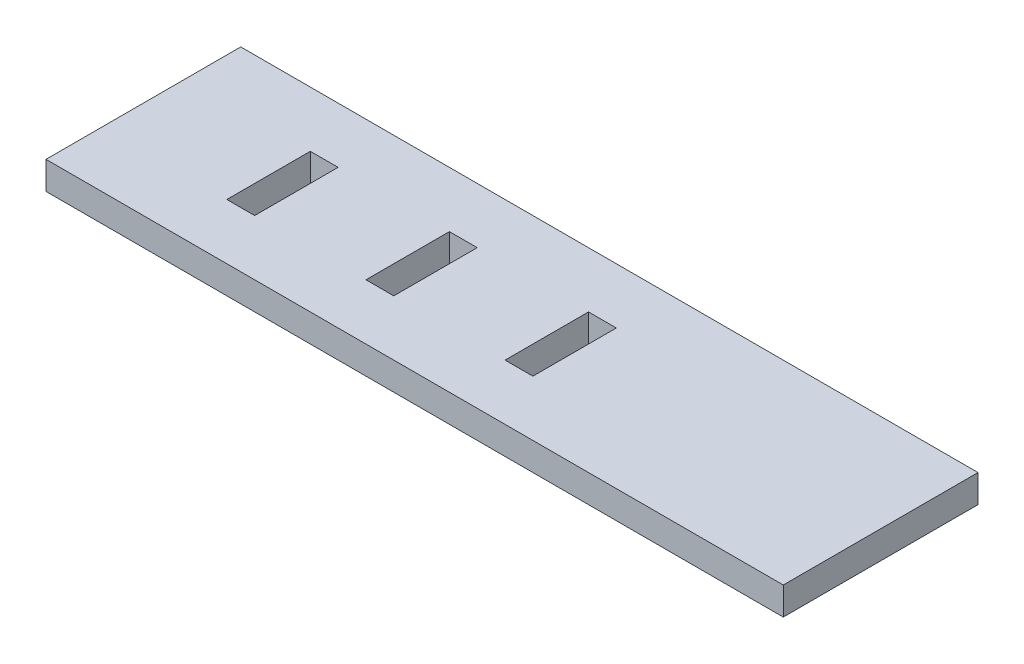
SolidWorks part; units mm, degrees
ref_plane "Front Plane" through (0, 0, 0) normal (0, 0, 1) x (1, 0, 0)
ref_plane "Top Plane" through (0, 0, 0) normal (0, 1, 0) x (1, 0, 0)
ref_plane "Right Plane" through (0, 0, 0) normal (1, 0, 0) x (0, 0, -1)
sketch "Sketch1" plane through (0, 0, 0) normal (0, 1, 0) x (1, 0, 0)
  line L1 (-98.4247, 43.4932) -> (166.5753, 43.4932)
  line L2 (-98.4247, 43.4932) -> (-98.4247, -26.5068)
  line L3 (-98.4247, -26.5068) -> (166.5753, -26.5068)
  line L4 (166.5753, 43.4932) -> (166.5753, -26.5068)
  line L6 (-53.4247, 23.4932) -> (-43.4247, 23.4932)
  line L7 (-53.4247, 23.4932) -> (-53.4247, -6.5068)
  line L8 (-53.4247, -6.5068) -> (-43.4247, -6.5068)
  line L9 (-43.4247, 23.4932) -> (-43.4247, -6.5068)
  line L13 (6.5753, 23.4932) -> (-3.4247, 23.4932)
  line L14 (6.5753, 23.4932) -> (6.5753, -6.5068)
  line L15 (6.5753, -6.5068) -> (-3.4247, -6.5068)
  line L16 (-3.4247, 23.4932) -> (-3.4247, -6.5068)
  line L21 (46.5753, 23.4932) -> (56.5753, 23.4932)
  line L22 (46.5753, 23.4932) -> (46.5753, -6.5068)
  line L23 (46.5753, -6.5068) -> (56.5753, -6.5068)
  line L24 (56.5753, 23.4932) -> (56.5753, -6.5068)
  dimension "D1" = 70
  dimension "D2" = 265
  dimension "D4" = 10
  dimension "D5" = 30
  dimension "D7" = 10
  dimension "D8" = 30
  dimension "D9" = 10
  dimension "30" = 30
extrude "Boss-Extrude1" add sketch "Sketch1" along normal blind 10
